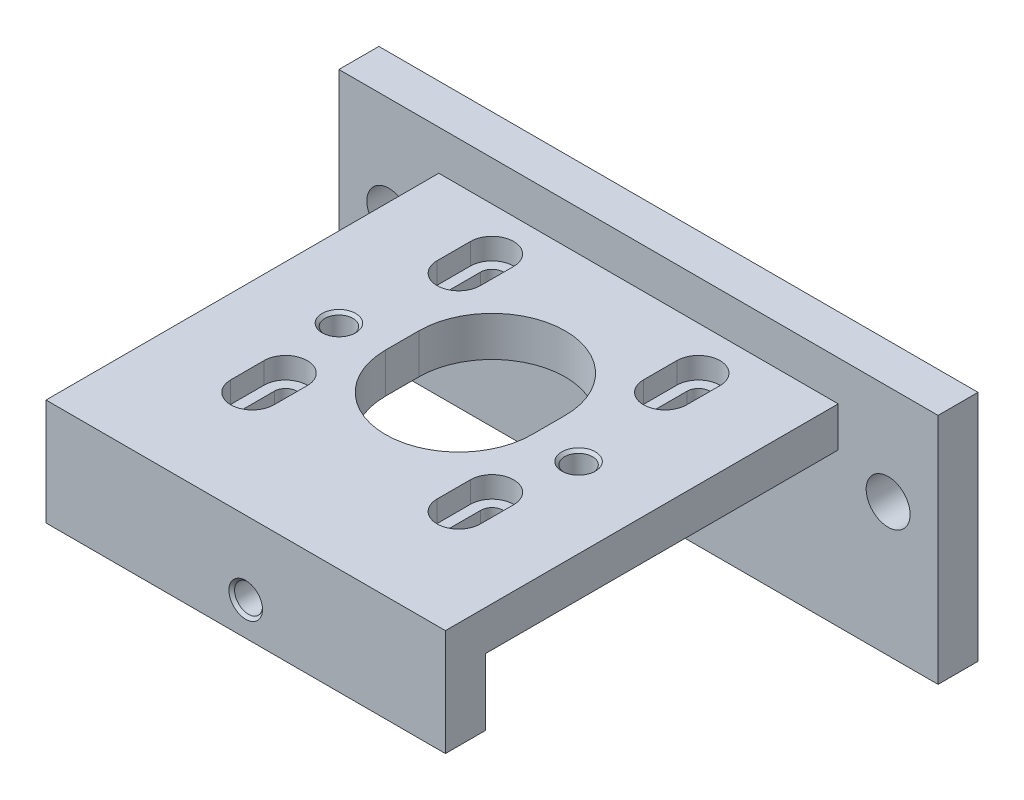
SolidWorks part; units mm, degrees
ref_plane "Front Plane" through (0, 0, 0) normal (0, 0, 1) x (1, 0, 0)
ref_plane "Top Plane" through (0, 0, 0) normal (0, 1, 0) x (1, 0, 0)
ref_plane "Right Plane" through (0, 0, 0) normal (1, 0, 0) x (0, 0, -1)
sketch "Sketch1" plane through (0, 0, 0) normal (1, 0, 0) x (0, 0, -1)
  line L1 (-60, 0) -> (-60, -16)
  line L2 (-60, -16) -> (-54, -16)
  line L3 (-54, -16) -> (-54, -6)
  line L4 (-54, -6) -> (-1, -6)
  line L5 (-1, -6) -> (-1, -29)
  line L6 (-1, -29) -> (5, -29)
  line L7 (5, -29) -> (5, 6)
  line L8 (5, 6) -> (-1, 6)
  line L9 (-1, 6) -> (-1, 0)
  line L10 (-1, 0) -> (-60, 0)
  dimension "D1" = 65
  dimension "D2" = 6
  dimension "D3" = 6
  dimension "D4" = 35
  dimension "D5" = 10
  dimension "D6" = 29
  dimension "D7" = 6
extrude "Boss-Extrude1" add sketch "Sketch1" along normal blind 90
sketch "Sketch3" plane through (0, -16, 0) normal (0, -1, 0) x (1, 0, 0)
  line L0 (90, 1) -> (0, 1) construction
  line L1 (75, 60) -> (75, 1)
  line L2 (90, 1) -> (75, 1)
  line L3 (90, 60) -> (90, 1)
  line L4 (90, 60) -> (75, 60)
  line L5 (0, 60) -> (15, 60)
  line L6 (0, 60) -> (0, 1)
  line L7 (0, 1) -> (15, 1)
  line L8 (15, 60) -> (15, 1)
  line L10 (90, 60) -> (0, 60) construction
  line L11 (45, -5) -> (45, 60) construction
  line L12 (90, -5) -> (0, -5) construction
  line L13 (0, 54) -> (0, 1) construction
  dimension "D1" = 60
extrude "Cut-Extrude1" cut sketch "Sketch3" against normal through all
hole_wizard "M6 Clearance Hole1" positions "Sketch5" profile "Sketch4" hole size "M6" standard "ISO" end condition through all
sketch "Sketch5" plane through (0, 0, 1) normal (0, 0, 1) x (1, 0, 0)
  line L0 (45, -29) -> (45, 6) construction
  line L1 (90, -29) -> (0, -29) construction
  line L2 (90, 6) -> (0, 6) construction
  point P0 (7.5, -9)
  point P12 (82.5, -9)
  dimension "D1" = 75
  dimension "D2" = 20
sketch "Sketch4" plane through (7.5, -9, 1) normal (1, 0, 0) x (0, -1, 0)
  line L0 (0, 0) -> (0, 6)
  line L1 (0, 6) -> (3.3, 6)
  line L2 (3.3, 6) -> (3.3, 0)
  line L5 (3.3, 0) -> (0, 0)
  line L11 (0, -6.35) -> (0, 107.95) construction
  dimension "Thru Hole Dia." = 6.6
  dimension "Thru Hole Depth" = 6
hole_wizard "M5 Tapped Hole1" positions "Sketch7" profile "Sketch6" tap size "M5" standard "ISO"
sketch "Sketch7" plane through (0, 0, 60) normal (0, 0, 1) x (1, 0, 0)
  line L0 (45, -16) -> (45, 0) construction
  line L1 (75, -16) -> (15, -16) construction
  line L2 (75, 0) -> (15, 0) construction
  point P0 (45, -11)
  dimension "D1" = 5
sketch "Sketch6" plane through (45, -11, 60) normal (1, 0, 0) x (0, -1, 0)
  line L0 (0, 0) -> (0, 6)
  line L1 (0, 6) -> (2.1, 6)
  line L2 (2.1, 6) -> (2.1, 0.425)
  line L3 (2.1, 0.425) -> (2.525, 0)
  line L5 (2.525, 0) -> (0, 0)
  line L6 (-2.1, 0.425) -> (-2.525, 0) construction
  line L11 (0, -6.35) -> (0, 107.95) construction
  dimension "Thru Tap Drill Dia." = 4.2
  dimension "Thru Tap Drill Depth" = 6
  dimension "Near C'Sink Dia." = 5.05
  dimension "Near C'Sink Angle" = 90
cosmetic thread "Hole Thread1" parameters "D2"=5
sketch "Sketch9" plane through (0, 0, 0) normal (0, 1, 0) x (1, 0, 0)
  line L0 (75, -28) -> (15, -28) construction
  line L1 (75, -60) -> (75, -1) construction
  line L2 (45, -1) -> (45, -60) construction
  line L3 (90, -1) -> (0, -1) construction
  line L4 (75, -60) -> (15, -60) construction
  line L5 (15, -1) -> (15, -60) construction
  line L6 (34, -28) -> (34, -23)
  line L7 (56, -23) -> (56, -28)
  arc A0 (34, -28) -> (56, -28) centre (45, -28) ccw
  arc A1 (34, -23) -> (56, -23) centre (45, -23) cw
  dimension "D2" = 11
  dimension "D1" = 27
  dimension "D3" = 2
extrude "Cut-Extrude2" cut sketch "Sketch9" against normal through all
hole_wizard "M5 Tapped Hole2" positions "Sketch12" profile "Sketch11" tap size "M5" standard "ISO" end condition through all
sketch "Sketch12" plane through (0, 0, 0) normal (0, 1, 0) x (-1, 0, 0)
  line L0 (-45, 1) -> (-45, 60) construction
  line L1 (-75, 1) -> (-15, 1) construction
  line L2 (-75, 60) -> (-15, 60) construction
  point P0 (-27, 28)
  point P11 (-63, 28)
  dimension "D1" = 36
sketch "Sketch11" plane through (27, 0, 28) normal (1, 0, 0) x (0, 0, 1)
  line L0 (0, 0) -> (0, 29)
  line L1 (0, 29) -> (2.1, 29)
  line L2 (2.1, 29) -> (2.1, 0.425)
  line L3 (2.1, 0.425) -> (2.525, 0)
  line L5 (2.525, 0) -> (0, 0)
  line L6 (-2.1, 0.425) -> (-2.525, 0) construction
  line L11 (0, -6.35) -> (0, 107.95) construction
  dimension "Thru Tap Drill Dia." = 4.2
  dimension "Thru Tap Drill Depth" = 29
  dimension "Near C'Sink Dia." = 5.05
  dimension "Near C'Sink Angle" = 90
cosmetic thread "Hole Thread2" parameters "D2"=5
cosmetic thread "Hole Thread3" parameters "D2"=5
hole_wizard "CBORE for M3 Hex Socket Head Cap Screw1" positions "Sketch14" profile "Sketch13" counterbore size "M3" standard "ISO" end condition through all
sketch "Sketch14" plane through (0, 0, 0) normal (0, 1, 0) x (-1, 0, 0)
  line L0 (-45, 1) -> (-45, 60) construction
  line L1 (-75, 1) -> (-15, 1) construction
  line L2 (-75, 60) -> (-15, 60) construction
  line L4 (-15, 28) -> (-75, 28) construction
  line L5 (-15, 1) -> (-15, 60) construction
  line L6 (-75, 60) -> (-75, 1) construction
  point P0 (-29.5, 12.5)
  point P27 (-60.5, 12.5)
  point P28 (-29.5, 43.5)
  point P29 (-60.5, 43.5)
  dimension "D3" = 31
  dimension "D4" = 31
  dimension "D1" = 2
  dimension "D2" = 2
sketch "Sketch13" plane through (29.5, 0, 12.5) normal (1, 0, 0) x (0, 0, 1)
  line L0 (0, 0) -> (0, 29)
  line L1 (0, 29) -> (1.7, 29)
  line L3 (1.7, 29) -> (1.7, 3)
  line L4 (1.7, 3) -> (3.25, 3)
  line L5 (3.25, 3) -> (3.25, 0)
  line L7 (3.25, 0) -> (0, 0)
  line L11 (0, -6.35) -> (0, 107.95) construction
  dimension "Thru Hole Dia." = 3.4
  dimension "Thru Hole Depth" = 29
  dimension "C'Bore Dia." = 6.5
  dimension "C'Bore Depth" = 3
sketch "Sketch15" plane through (0, 0, 0) normal (0, 1, 0) x (1, 0, 0)
  line L0 (29.5, -12.5) -> (29.5, -7.5) construction
  line L1 (27.8, -12.5) -> (27.8, -7.5)
  line L2 (31.2, -12.5) -> (31.2, -7.5)
  line L3 (60.5, -12.5) -> (60.5, -7.5) construction
  line L4 (58.8, -12.5) -> (58.8, -7.5)
  line L5 (62.2, -12.5) -> (62.2, -7.5)
  line L6 (64.7763, -56.7649) -> (64.7763, -2.7649) construction
  line L9 (29.5, -43.5) -> (29.5, -38.5) construction
  line L10 (27.8, -43.5) -> (27.8, -38.5)
  line L11 (31.2, -43.5) -> (31.2, -38.5)
  line L12 (60.5, -43.5) -> (60.5, -38.5) construction
  line L13 (58.8, -43.5) -> (58.8, -38.5)
  line L14 (62.2, -43.5) -> (62.2, -38.5)
  arc A0 (27.8, -12.5) -> (31.2, -12.5) centre (29.5, -12.5) ccw
  arc A1 (31.2, -7.5) -> (27.8, -7.5) centre (29.5, -7.5) ccw
  arc A2 (58.8, -12.5) -> (62.2, -12.5) centre (60.5, -12.5) ccw
  arc A3 (62.2, -7.5) -> (58.8, -7.5) centre (60.5, -7.5) ccw
  circle A4 centre (29.5, -12.5) radius 1.7 construction
  arc A7 (27.8, -43.5) -> (31.2, -43.5) centre (29.5, -43.5) ccw
  arc A8 (31.2, -38.5) -> (27.8, -38.5) centre (29.5, -38.5) ccw
  arc A9 (58.8, -43.5) -> (62.2, -43.5) centre (60.5, -43.5) ccw
  arc A10 (62.2, -38.5) -> (58.8, -38.5) centre (60.5, -38.5) ccw
  point P3 (29.5, -10)
  point P13 (60.5, -10)
  point P28 (29.5, -41)
  point P35 (60.5, -41)
  dimension "D1" = 5
  dimension "D4" = 31
  dimension "D5" = 31
  dimension "D2" = 2
  dimension "D3" = 2
extrude "Cut-Extrude3" cut sketch "Sketch15" against normal through all
sketch "Sketch16" plane through (0, 0, 0) normal (0, 1, 0) x (1, 0, 0)
  line L0 (29.5, -12.5) -> (29.5, -7.5) construction
  line L1 (26.25, -12.5) -> (26.25, -7.5)
  line L2 (32.75, -12.5) -> (32.75, -7.5)
  line L3 (60.5, -12.5) -> (60.5, -7.5) construction
  line L4 (57.25, -12.5) -> (57.25, -7.5)
  line L5 (63.75, -12.5) -> (63.75, -7.5)
  line L6 (29.5, -43.5) -> (29.5, -38.5) construction
  line L7 (26.25, -43.5) -> (26.25, -38.5)
  line L8 (32.75, -43.5) -> (32.75, -38.5)
  line L9 (60.5, -43.5) -> (60.5, -38.5) construction
  line L10 (57.25, -43.5) -> (57.25, -38.5)
  line L11 (63.75, -43.5) -> (63.75, -38.5)
  arc A0 (26.25, -12.5) -> (32.75, -12.5) centre (29.5, -12.5) ccw
  arc A1 (32.75, -7.5) -> (26.25, -7.5) centre (29.5, -7.5) ccw
  arc A2 (27.8, -9.7301) -> (31.2, -9.7301) centre (29.5, -12.5) ccw construction
  arc A3 (57.25, -12.5) -> (63.75, -12.5) centre (60.5, -12.5) ccw
  arc A4 (63.75, -7.5) -> (57.25, -7.5) centre (60.5, -7.5) ccw
  arc A5 (26.25, -43.5) -> (32.75, -43.5) centre (29.5, -43.5) ccw
  arc A6 (32.75, -38.5) -> (26.25, -38.5) centre (29.5, -38.5) ccw
  arc A7 (57.25, -43.5) -> (63.75, -43.5) centre (60.5, -43.5) ccw
  arc A8 (63.75, -38.5) -> (57.25, -38.5) centre (60.5, -38.5) ccw
  point P4 (29.5, -10)
  point P16 (60.5, -10)
  point P23 (29.5, -41)
  point P30 (60.5, -41)
  dimension "D1" = 2
  dimension "D2" = 2
extrude "Cut-Extrude4" cut sketch "Sketch16" against normal blind 3.2
